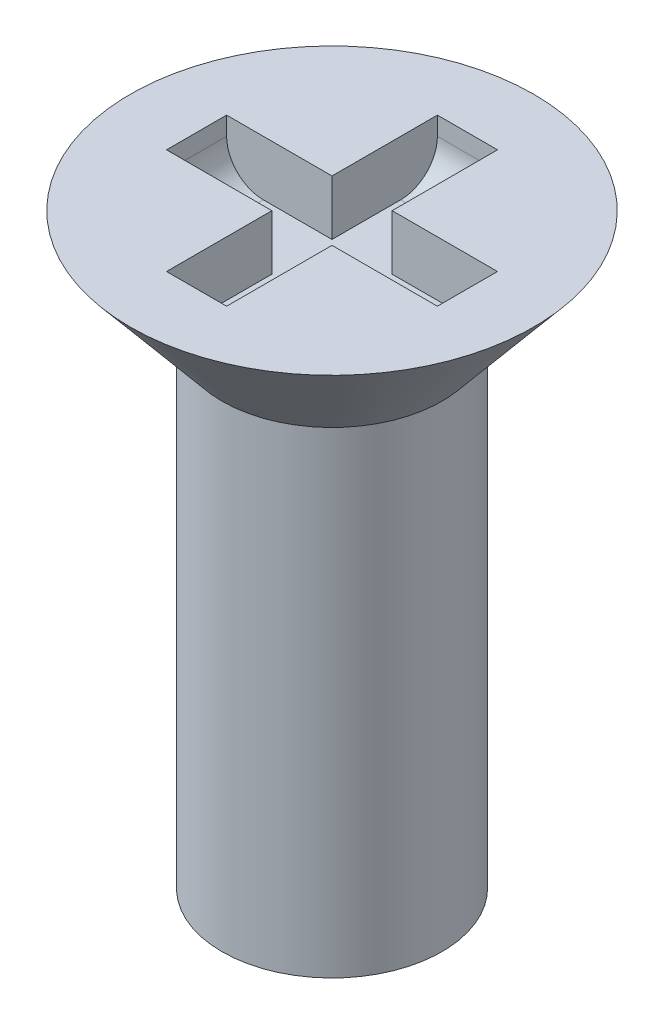
SolidWorks part; units mm, degrees
ref_plane "Front Plane" through (0, 0, 0) normal (0, 0, 1) x (1, 0, 0)
ref_plane "Top Plane" through (0, 0, 0) normal (0, 1, 0) x (1, 0, 0)
ref_plane "Right Plane" through (0, 0, 0) normal (1, 0, 0) x (0, 0, -1)
sketch "Sketch1" plane through (0, 0, 0) normal (0, 1, 0) x (1, 0, 0)
  circle A0 centre (0, 0) radius 3
extrude "Boss-Extrude1" add sketch "Sketch1" along normal blind 13
sketch "Sketch3" plane through (0, 0, 0) normal (0, 0, 1) x (1, 0, 0)
  line L0 (3, 13) -> (-3, 13) construction
  line L2 (0, 13) -> (0, 16)
  line L3 (-3, 13) -> (0, 13)
  line L6 (-3, 13) -> (-5.5, 16)
  line L7 (-5.5, 16) -> (0, 16)
  dimension "D1" = 3
  dimension "D2" = 5.5
  dimension "D3" = 3
  dimension "D4" = 50.194
revolve "Revolve2" add sketch "Sketch3" angle 360 about L2
sketch "Sketch4" plane through (0, 16, 0) normal (0, 1, 0) x (1, 0, 0)
  line L0 (-0.8196, 0.8196) -> (-3.6931, 0.8196)
  line L1 (0.8196, 3.6931) -> (-0.8196, 3.6931)
  line L2 (0.8196, 3.6931) -> (0.8196, 0.8196)
  line L3 (0.8196, -3.6931) -> (-0.8196, -3.6931)
  line L4 (-0.8196, 3.6931) -> (-0.8196, 0.8196)
  line L5 (0.8196, -0.8196) -> (0.8196, -3.6931)
  line L7 (3.6931, 0.8196) -> (0.8196, 0.8196)
  line L8 (3.6931, 0.8196) -> (3.6931, -0.8196)
  line L9 (3.6931, -0.8196) -> (0.8196, -0.8196)
  line L10 (-3.6931, 0.8196) -> (-3.6931, -0.8196)
  line L14 (-0.8196, -0.8196) -> (-3.6931, -0.8196)
  line L15 (-0.8196, -0.8196) -> (-0.8196, -3.6931)
  point P0 (0, 0)
  point P6 (0, 0)
extrude "Cut-Extrude1" cut sketch "Sketch4" against normal blind 1.5
fillet "Fillet1" radius 1 1 edges at (0, 14.5, -3.6931)
fillet "Fillet2" radius 1 1 edges at (3.6931, 14.5, 0)
fillet "Fillet3" radius 1 1 edges at (0, 14.5, 3.6931)
fillet "Fillet4" radius 1 1 edges at (-3.6931, 14.5, 0)
